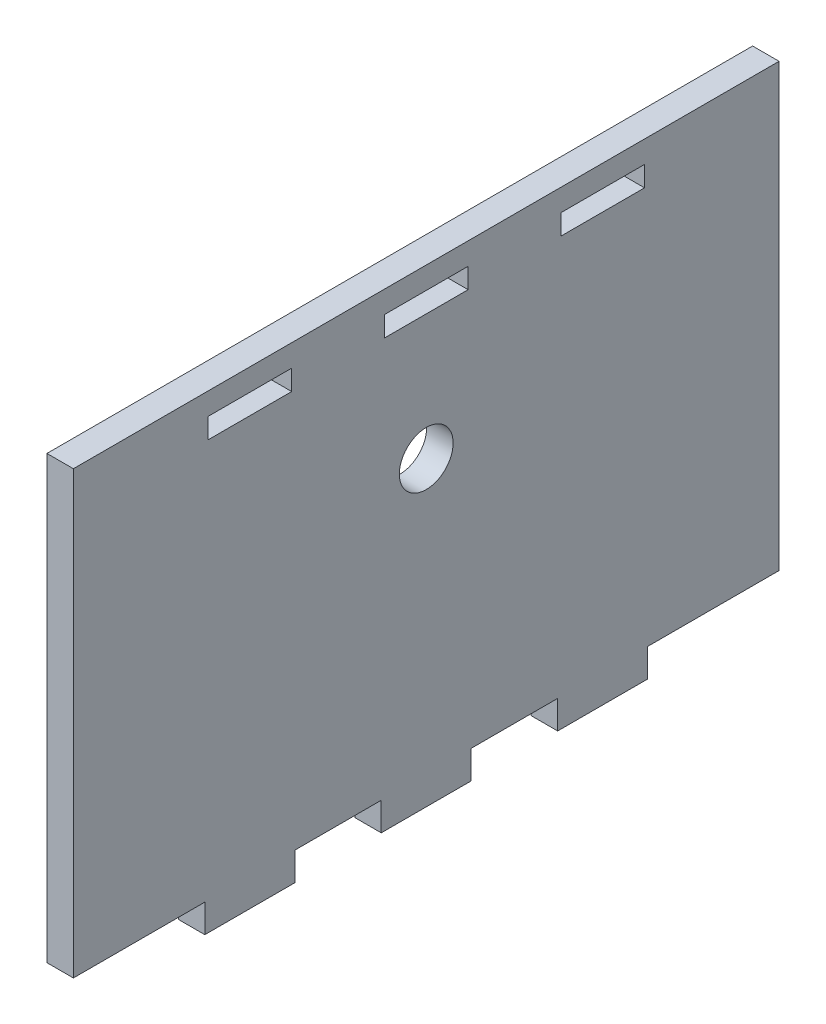
SolidWorks part; units mm, degrees
ref_plane "Alzado" through (0, 0, 0) normal (0, 0, 1) x (1, 0, 0)
ref_plane "Planta" through (0, 0, 0) normal (0, 1, 0) x (1, 0, 0)
ref_plane "Vista lateral" through (0, 0, 0) normal (1, 0, 0) x (0, 0, -1)
sketch "Croquis1" plane through (0, 0, 0) normal (1, 0, 0) x (0, 0, -1)
  line L0 (-14.9, -25) -> (-5.1, -25)
  line L1 (-40, 25) -> (40, 25)
  line L2 (-40, 25) -> (-40, -25)
  line L3 (-40, -25) -> (-25.1, -25)
  line L4 (40, 25) -> (40, -25)
  line L5 (-40, 25) -> (40, -25) construction
  line L6 (-40, -25) -> (40, 25) construction
  line L8 (-25.1, -25) -> (-25.1, -28.2)
  line L9 (-25.1, -28.2) -> (-14.9, -28.2)
  line L10 (-14.9, -25) -> (-14.9, -28.2)
  line L12 (-5.1, -25) -> (-5.1, -28.2)
  line L13 (-5.1, -28.2) -> (5.1, -28.2)
  line L14 (5.1, -25) -> (5.1, -28.2)
  line L16 (14.9, -25) -> (14.9, -28.2)
  line L17 (14.9, -28.2) -> (25.1, -28.2)
  line L18 (25.1, -25) -> (25.1, -28.2)
  line L19 (-24.75, 22.5) -> (-15.25, 22.5)
  line L20 (-24.75, 22.5) -> (-24.75, 20.2)
  line L21 (-24.75, 20.2) -> (-15.25, 20.2)
  line L22 (-15.25, 22.5) -> (-15.25, 20.2)
  line L23 (5.1, -25) -> (14.9, -25)
  line L24 (25.1, -25) -> (40, -25)
  line L25 (0, 0) -> (0, -8.3664) construction
  line L26 (-4.75, 20.2) -> (4.75, 20.2)
  line L27 (-4.75, 20.2) -> (-4.75, 22.5)
  line L28 (-4.75, 22.5) -> (4.75, 22.5)
  line L29 (4.75, 20.2) -> (4.75, 22.5)
  line L30 (24.75, 20.2) -> (15.25, 20.2)
  line L31 (15.25, 22.5) -> (15.25, 20.2)
  line L32 (24.75, 22.5) -> (15.25, 22.5)
  line L33 (24.75, 22.5) -> (24.75, 20.2)
  circle A1 centre (0, 6) radius 3.05
  point P0 (0, 0)
  point P10 (-20, -28.2)
  point P15 (0, -28.2)
  point P20 (20, -28.2)
  point P25 (-20, 22.5)
  point P30 (0, 20.2)
  point P31 (-20, 20.2)
  dimension "D20" = 6.1
  dimension "D1" = 50
  dimension "D2" = 80
  dimension "D3" = 3.2
  dimension "D4" = 10.2
  dimension "D5" = 20
  dimension "D6" = 3.2
  dimension "D7" = 10.2
  dimension "D8" = 20
  dimension "D9" = 3.2
  dimension "D10" = 10.2
  dimension "D11" = 20
  dimension "D12" = 2.3
  dimension "D13" = 9.5
  dimension "D14" = 2.5
  dimension "D15" = 20
  dimension "D16" = 2.3
  dimension "D17" = 9.5
  dimension "D18" = 20
  dimension "D19" = 2.5
  dimension "D21" = 6
extrude "Saliente-Extruir1" add sketch "Croquis1" along normal blind 3
